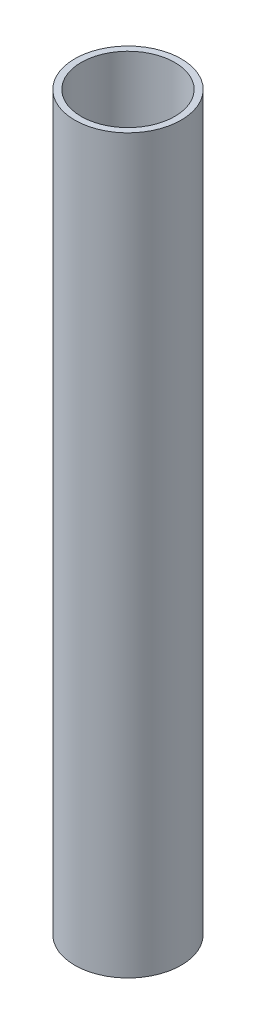
SolidWorks part; units mm, degrees
material "Thornel Mat VMA"
ref_plane "前视基准面" through (0, 0, 0) normal (0, 0, 1) x (1, 0, 0)
ref_plane "上视基准面" through (0, 0, 0) normal (0, 1, 0) x (1, 0, 0)
ref_plane "右视基准面" through (0, 0, 0) normal (1, 0, 0) x (0, 0, -1)
sketch "草图1" plane through (0, 0, 0) normal (0, 1, 0) x (1, 0, 0)
  circle A0 centre (0, 0) radius 12.5
  circle A1 centre (0, 0) radius 11
  dimension "D1" = 25
  dimension "D2" = 22
extrude "凸台-拉伸1" add sketch "草图1" along normal blind 172
